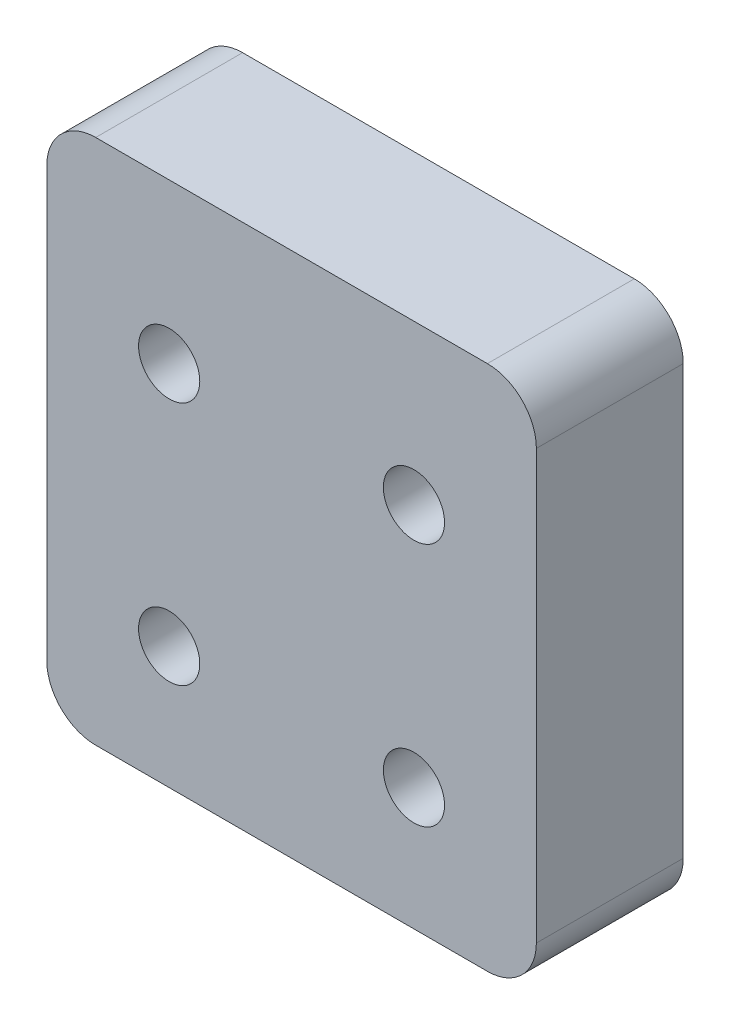
SolidWorks part; units mm, degrees
ref_plane "Front" through (0, 0, 0) normal (0, 0, 1) x (1, 0, 0)
ref_plane "Top" through (0, 0, 0) normal (0, 1, 0) x (1, 0, 0)
ref_plane "Right" through (0, 0, 0) normal (1, 0, 0) x (0, 0, -1)
sketch "Esquisse1" plane through (0, 0, 0) normal (0, 0, 1) x (1, 0, 0)
  line L1 (0, 0) -> (40, 0)
  line L2 (0, 0) -> (0, 43)
  line L3 (0, 43) -> (40, 43)
  line L4 (40, 0) -> (40, 43)
  dimension "D1" = 43
  dimension "D2" = 40
extrude "Boss.-Extru.1" add sketch "Esquisse1" along normal blind 12
sketch "Esquisse2" plane through (0, 0, 12) normal (0, 0, 1) x (1, 0, 0)
  line L0 (20, 43) -> (20, 0) construction
  line L1 (40, 43) -> (0, 43) construction
  line L2 (0, 0) -> (40, 0) construction
  line L3 (0, 20) -> (40, 20) construction
  line L4 (0, 43) -> (0, 0) construction
  line L5 (40, 0) -> (40, 43) construction
  circle A0 centre (10, 30) radius 2.5
  circle A1 centre (10, 10) radius 2.5
  circle A2 centre (30, 10) radius 2.5
  circle A3 centre (30, 30) radius 2.5
  dimension "D1" = 5
  dimension "D2" = 20
  dimension "D3" = 20
  dimension "D4" = 20
extrude "Enlèv. mat.-Extru.1" cut sketch "Esquisse2" against normal through all
fillet "Congé1" radius 4 4 edges at (40, 43, 6) (40, 0, 6) (0, 0, 6) (0, 43, 6)
